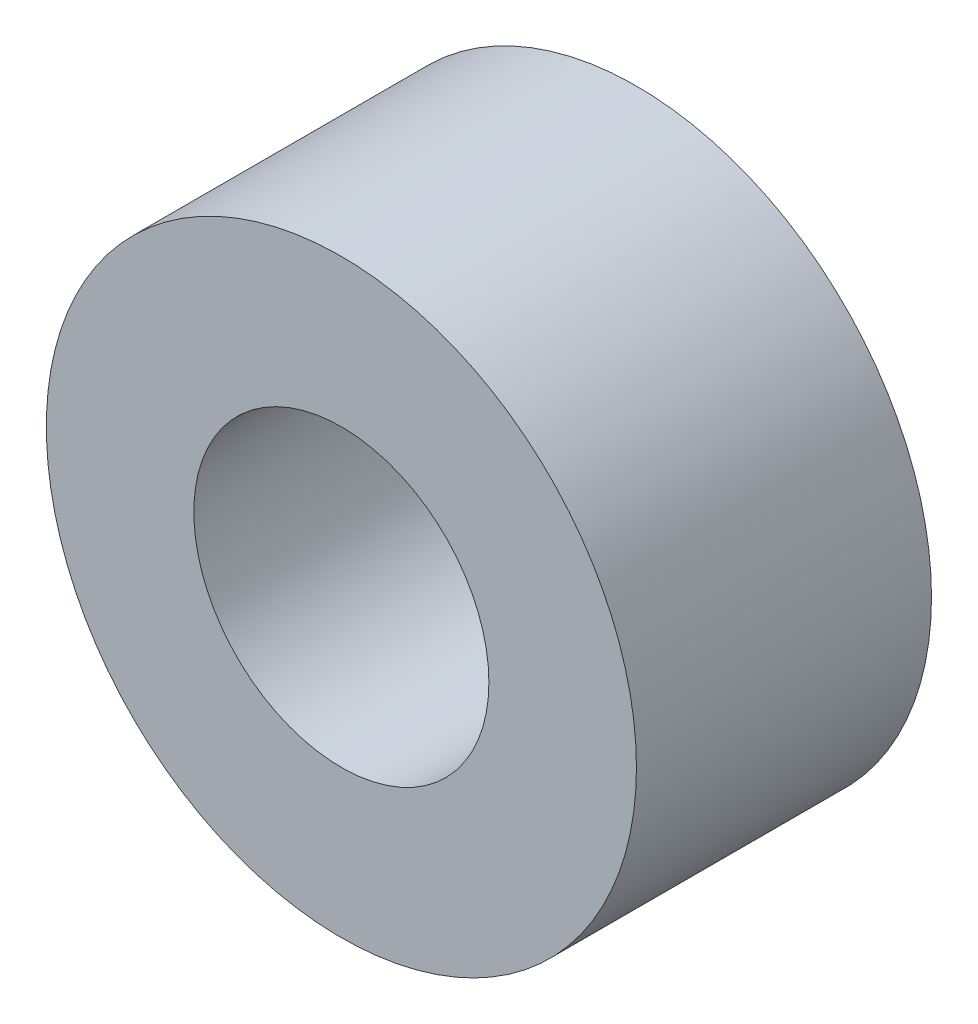
SolidWorks part; units mm, degrees
ref_plane "Front Plane" through (0, 0, 0) normal (0, 0, 1) x (1, 0, 0)
ref_plane "Top Plane" through (0, 0, 0) normal (0, 1, 0) x (1, 0, 0)
ref_plane "Right Plane" through (0, 0, 0) normal (1, 0, 0) x (0, 0, -1)
sketch "Sketch1" plane through (0, 0, 0) normal (0, 0, 1) x (1, 0, 0)
  circle A0 centre (0, 0) radius 6.35
  dimension "D1" = 12.7
extrude "Boss-Extrude1" add sketch "Sketch1" along normal blind 6.35
sketch "Sketch2" plane through (0, 0, 6.35) normal (0, 0, 1) x (1, 0, 0)
  circle A0 centre (0, 0) radius 3.175
  dimension "D1" = 6.35
extrude "Cut-Extrude1" cut sketch "Sketch2" against normal blind 6.35
